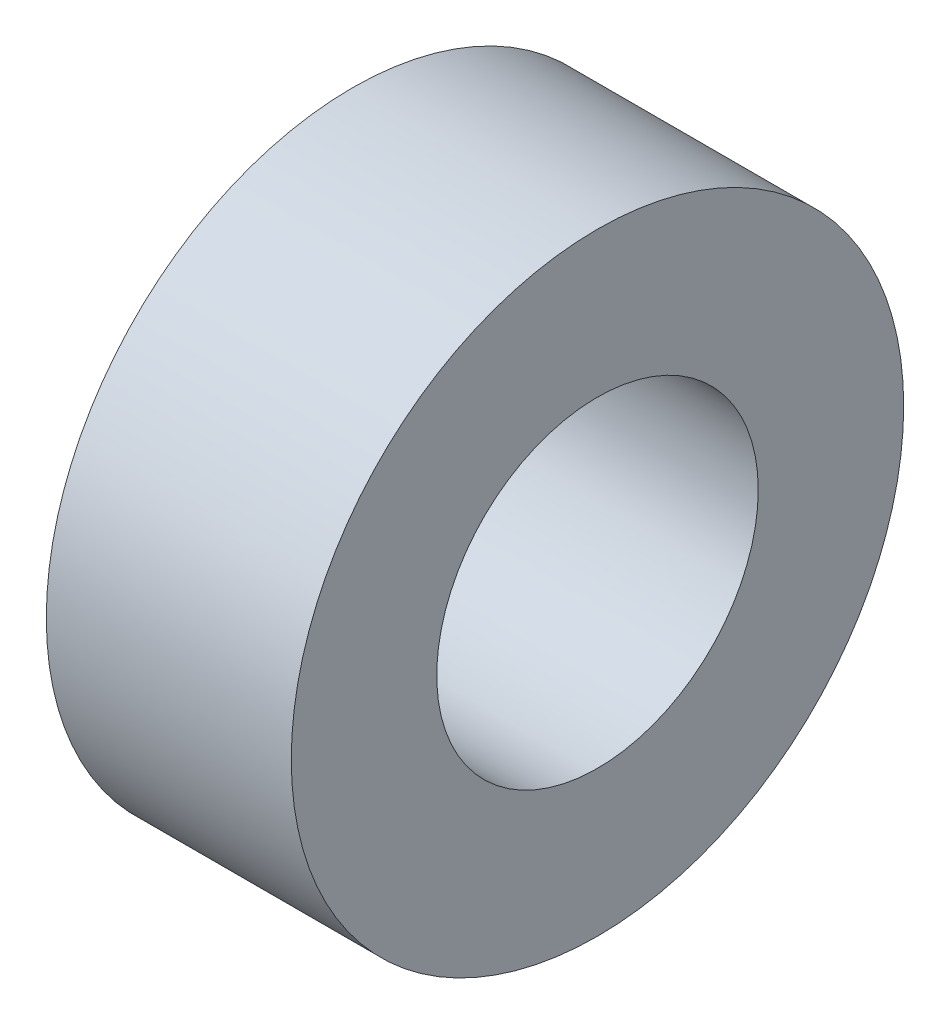
SolidWorks part; units mm, degrees
ref_plane "Plan de face" through (0, 0, 0) normal (0, 0, 1) x (1, 0, 0)
ref_plane "Plan de dessus" through (0, 0, 0) normal (0, 1, 0) x (1, 0, 0)
ref_plane "Plan de droite" through (0, 0, 0) normal (1, 0, 0) x (0, 0, -1)
sketch "Esquisse1" plane through (0, 0, 0) normal (0, 1, 0) x (1, 0, 0)
  line L0 (0, 0) -> (8, 0)
  line L1 (8, 0) -> (8, 10)
  line L2 (8, 10) -> (0, 10)
  line L3 (0, 10) -> (0, 0)
  dimension "D1" = 10
  dimension "D2" = 8
revolve "Révolution1" add sketch "Esquisse1" angle 360 about L2
sketch "Esquisse2" plane through (8, 0, 0) normal (1, 0, 0) x (0, 0, -1)
  line L0 (0, 0) -> (20, 0) construction
  circle A0 centre (10, 0) radius 10 construction
  circle A1 centre (10, 0) radius 5.25
  dimension "D1" = 10.5
extrude "Enlèv. mat.-Extru.1" cut sketch "Esquisse2" against normal blind 10
